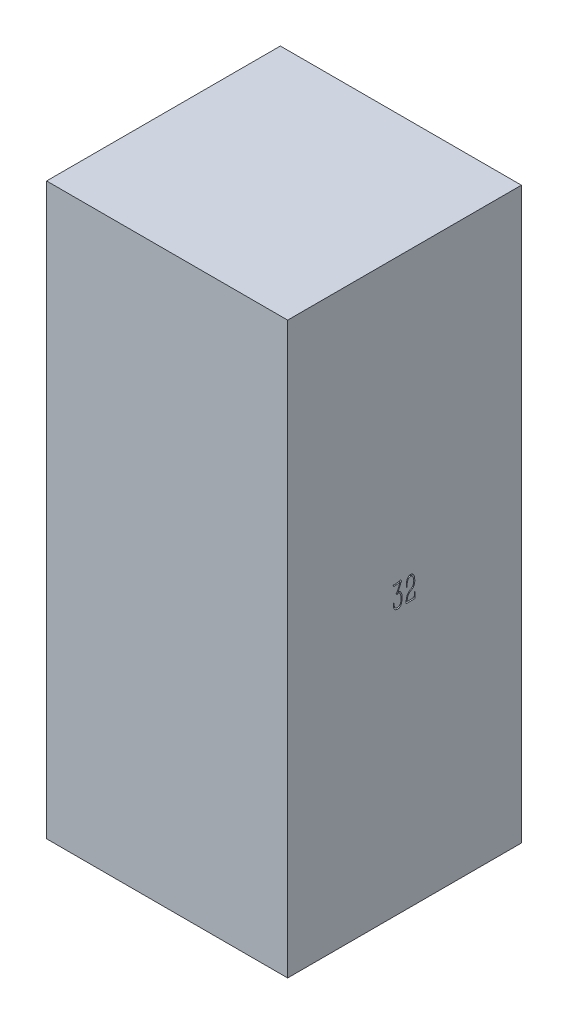
SolidWorks part; units mm, degrees
ref_plane "前视基准面" through (0, 0, 0) normal (0, 0, 1) x (1, 0, 0)
ref_plane "上视基准面" through (0, 0, 0) normal (0, 1, 0) x (1, 0, 0)
ref_plane "右视基准面" through (0, 0, 0) normal (1, 0, 0) x (0, 0, -1)
sketch "草图1" plane through (0, 0, 0) normal (0, 1, 0) x (1, 0, 0)
  line L1 (-16.5, 16) -> (16.5, 16)
  line L2 (-16.5, 16) -> (-16.5, -16)
  line L3 (-16.5, -16) -> (16.5, -16)
  line L4 (16.5, 16) -> (16.5, -16)
  line L5 (-16.5, 16) -> (16.5, -16) construction
  line L6 (-16.5, -16) -> (16.5, 16) construction
  point P0 (0, 0)
  dimension "D1" = 33
  dimension "D2" = 32
extrude "凸台-拉伸1" add sketch "草图1" along normal blind 78
sketch "草图2" plane through (16.5, 0, 0) normal (1, 0, 0) x (0, 0, -1)
  text T0 "32\r\n" font "汉仪长仿宋体" height 3.5
extrude "切除-拉伸1" cut sketch "草图2" against normal through all
